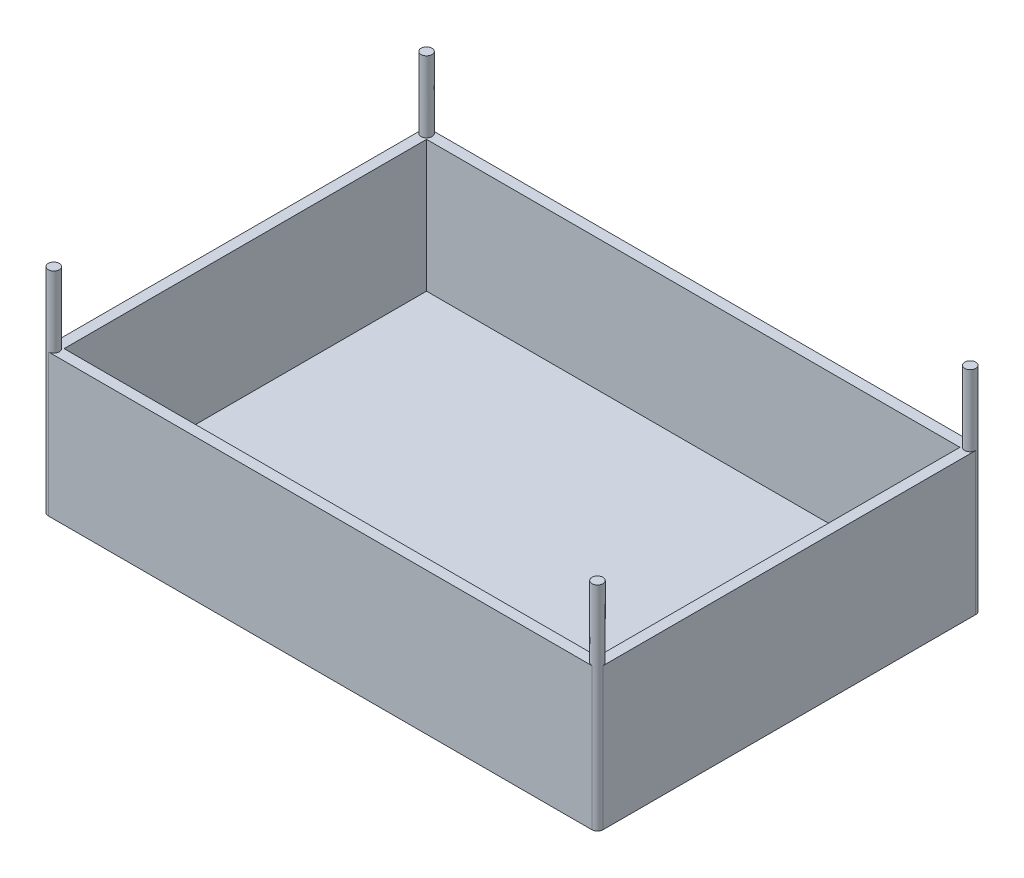
SolidWorks part; units mm, degrees
ref_plane "Front Plane" through (0, 0, 0) normal (0, 0, 1) x (1, 0, 0)
ref_plane "Top Plane" through (0, 0, 0) normal (0, 1, 0) x (1, 0, 0)
ref_plane "Right Plane" through (0, 0, 0) normal (1, 0, 0) x (0, 0, -1)
sketch "Sketch1" plane through (0, 0, 0) normal (0, 1, 0) x (1, 0, 0)
  circle A0 centre (-76.5, 52.45) radius 1.55
  circle A1 centre (76.5, 52.45) radius 1.55
  circle A2 centre (76.5, -52.45) radius 1.55
  circle A3 centre (-76.5, -52.45) radius 1.55
  point P0 (0, 0)
  dimension "D3" = 3.1
  dimension "D1" = 153
  dimension "D2" = 104.9
extrude "Boss-Extrude1" add sketch "Sketch1" along normal blind 60
sketch "Sketch2" plane through (0, 0, 0) normal (0, 1, 0) x (1, 0, 0)
  line L0 (-78.05, 52.45) -> (-78.05, -52.45)
  line L1 (-76.5, -54) -> (76.5, -54)
  line L2 (78.05, -52.45) -> (78.05, 52.45)
  line L3 (76.5, 54) -> (-76.5, 54)
  circle A0 centre (-76.5, 52.45) radius 1.55 construction
  circle A1 centre (-76.5, -52.45) radius 1.55 construction
  circle A2 centre (76.5, -52.45) radius 1.55 construction
  circle A3 centre (76.5, 52.45) radius 1.55 construction
  arc A4 (-78.05, 52.45) -> (-76.5, 54) centre (-76.5, 52.45) cw
  arc A5 (76.5, 54) -> (78.05, 52.45) centre (76.5, 52.45) cw
  arc A6 (78.05, -52.45) -> (76.5, -54) centre (76.5, -52.45) cw
  arc A7 (-78.05, -52.45) -> (-76.5, -54) centre (-76.5, -52.45) ccw
extrude "Boss-Extrude2" add sketch "Sketch2" along normal blind 40
shell "Shell1" thickness 3
